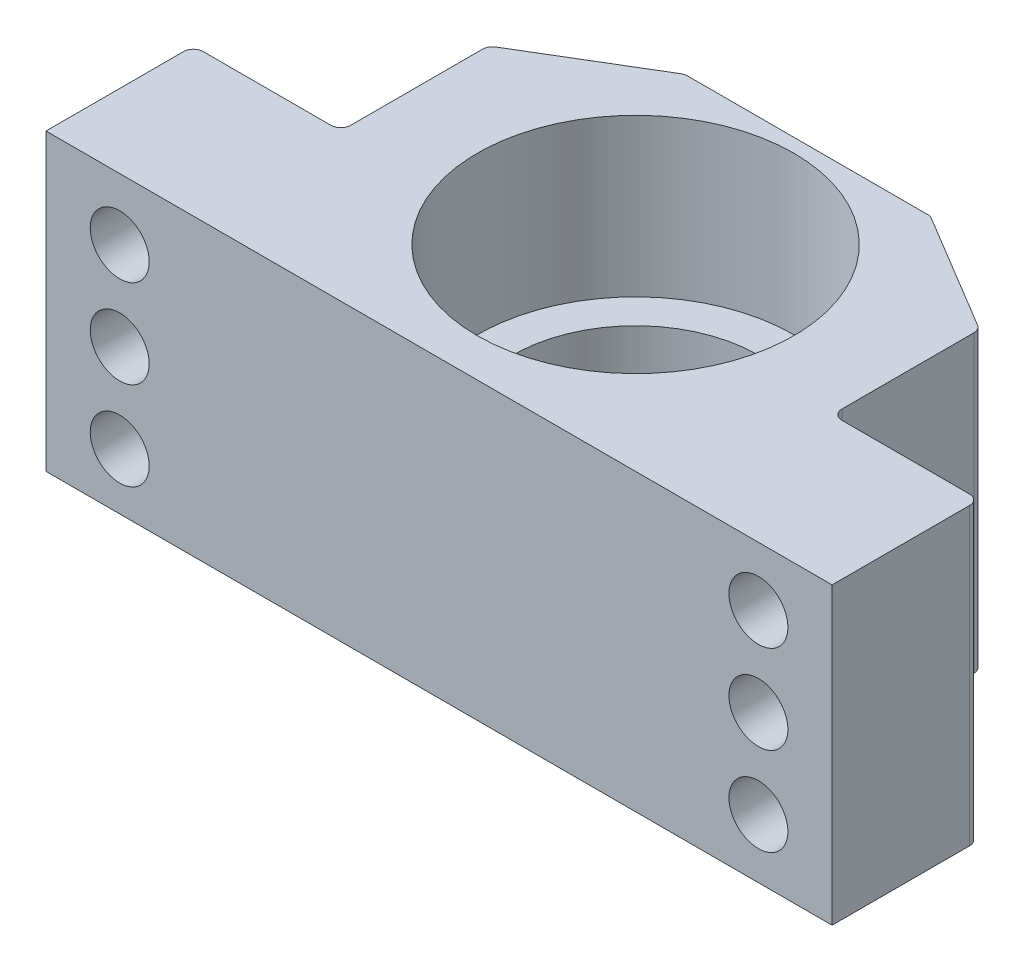
SolidWorks part; units mm, degrees
ref_plane "Front Plane" through (0, 0, 0) normal (0, 0, 1) x (1, 0, 0)
ref_plane "Top Plane" through (0, 0, 0) normal (0, 1, 0) x (1, 0, 0)
ref_plane "Right Plane" through (0, 0, 0) normal (1, 0, 0) x (0, 0, -1)
sketch "Sketch1" plane through (0, 0, 0) normal (0, 1, 0) x (1, 0, 0)
  line L0 (0, 0) -> (40, 0)
  line L1 (0, 0) -> (-40, 0)
  line L2 (-40, 0) -> (-40, 15)
  line L3 (40, 0) -> (40, 15)
  line L4 (-40, 15) -> (-25, 15)
  line L5 (40, 15) -> (25, 15)
  line L6 (-25, 15) -> (-25, 45)
  line L7 (25, 15) -> (25, 45)
  line L8 (-25, 45) -> (25, 45)
extrude "Boss-Extrude1" add sketch "Sketch1" along normal blind 30
sketch "Sketch2" plane through (0, 30, 0) normal (0, 1, 0) x (1, 0, 0)
  circle A0 centre (0, 20) radius 16.1
  dimension "D1" = 32.2
extrude "Cut-Extrude1" cut sketch "Sketch2" against normal blind 16
sketch "Sketch6" plane through (0, 0, 0) normal (0, -1, 0) x (1, 0, 0)
  circle A0 centre (0, -20) radius 12.5
extrude "Cut-Extrude2" cut sketch "Sketch6" against normal blind 14
sketch "Sketch8" plane through (0, 0, -15) normal (0, 0, -1) x (-1, 0, 0)
  circle A0 centre (-32.5, 6) radius 3
  circle A1 centre (-32.5, 15) radius 3
  circle A2 centre (-32.5, 24) radius 3
extrude "Cut-Extrude4" cut sketch "Sketch8" against normal blind 15
sketch "Sketch9" plane through (0, 0, -15) normal (0, 0, -1) x (-1, 0, 0)
  circle A0 centre (32.5, 23.7217) radius 3
  circle A1 centre (32.5, 14.7217) radius 3
  circle A2 centre (32.5, 5.7217) radius 3
extrude "Cut-Extrude5" cut sketch "Sketch9" against normal blind 15
sketch "Sketch11" plane through (0, 30, 0) normal (0, 1, 0) x (1, 0, 0)
  line L1 (-25, 45) -> (-25, 15) construction
  line L2 (-25, 30) -> (-25, 45)
  line L3 (-25, 45) -> (0, 45)
  line L4 (25, 45) -> (-25, 45) construction
  line L5 (0, 45) -> (-25, 30)
extrude "Cut-Extrude6" cut sketch "Sketch11" against normal blind 30
sketch "Sketch12" plane through (0, 30, 0) normal (0, 1, 0) x (1, 0, 0)
  line L1 (25, 15) -> (25, 45) construction
  line L2 (25, 30) -> (0, 45)
  line L3 (0, 45) -> (25, 45)
  line L4 (25, 45) -> (25, 30)
extrude "Cut-Extrude7" cut sketch "Sketch12" against normal blind 30
sketch "Sketch13" plane through (0, 30, 0) normal (0, 1, 0) x (1, 0, 0)
  line L1 (-25, 30) -> (0, 45) construction
  line L2 (-12.5, 37.5) -> (12.5, 37.5)
  line L3 (0, 45) -> (25, 30) construction
  line L4 (12.5, 37.5) -> (0, 45)
  line L5 (0, 45) -> (-12.5, 37.5)
extrude "Cut-Extrude8" cut sketch "Sketch13" against normal blind 30
fillet "Fillet2" radius 1 1 edges at (-25, 15, -15)
fillet "Fillet3" radius 1 7 edges at (-40, 15, -15) (40, 15, -15) (25, 15, -15) (25, 15, -30) (12.5, 15, -37.5) (-12.5, 15, -37.5) (-25, 15, -30)
